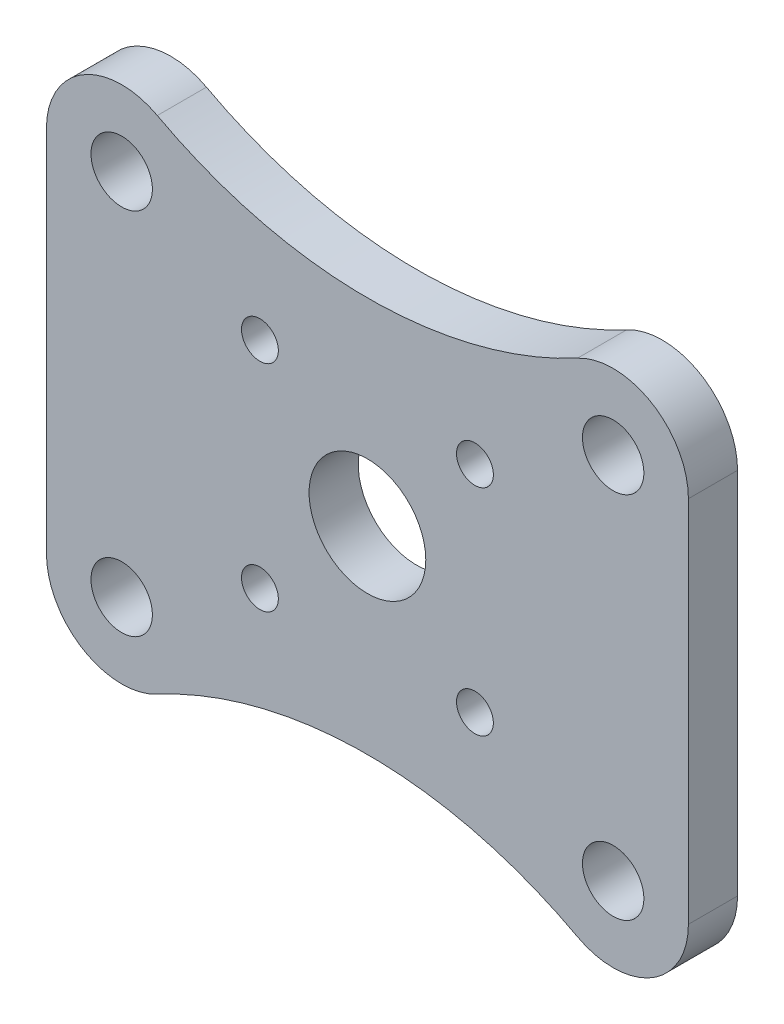
SolidWorks part; units mm, degrees
ref_plane "Front Plane" through (0, 0, 0) normal (0, 0, 1) x (1, 0, 0)
ref_plane "Top Plane" through (0, 0, 0) normal (0, 1, 0) x (1, 0, 0)
ref_plane "Right Plane" through (0, 0, 0) normal (1, 0, 0) x (0, 0, -1)
sketch "Sketch6" plane through (0, 0, 0) normal (0, 0, 1) x (1, 0, 0)
  line L0 (0, 16.0916) -> (0, 0) construction
  line L2 (0, 0) -> (0, -16.0916) construction
  line L3 (-26.1236, 15) -> (-26.1236, -15)
  line L4 (26.1236, 15) -> (26.1236, -15)
  circle A0 centre (-20, 15) radius 6.1236
  arc A1 (-17.102, 20.3945) -> (17.102, 20.3945) centre (0, 52.2292) ccw
  circle A2 centre (-20, -15) radius 6.1236
  arc A3 (-17.102, -20.3945) -> (17.102, -20.3945) centre (0, -52.2292) cw
  circle A6 centre (20, 15) radius 6.1236
  circle A7 centre (20, -15) radius 6.1236
extrude "Boss-Extrude1" add sketch "Sketch6" along normal blind 4 contours A7 L4 A6 A1 A0 L3 A2 A3 | A2 | A0 | A6 | A7
sketch "Sketch1" plane through (0, 0, 0) normal (0, 0, 1) x (1, 0, 0)
  line L0 (-8.75, 8.75) -> (8.75, 8.75) construction
  line L1 (8.75, 8.75) -> (8.75, -8.75) construction
  line L2 (8.75, -8.75) -> (-8.75, -8.75) construction
  line L3 (-8.75, -8.75) -> (-8.75, 8.75) construction
  line L4 (-8.75, 8.75) -> (8.75, -8.75) construction
  line L5 (8.75, 8.75) -> (-8.75, -8.75) construction
  circle A0 centre (-8.75, -8.75) radius 1.5
  circle A1 centre (-8.75, 8.75) radius 1.5
  circle A2 centre (8.75, 8.75) radius 1.5
  circle A3 centre (8.75, -8.75) radius 1.5
  circle A4 centre (0, 0) radius 4.75
  dimension "D7" = 3
  dimension "D13" = 9.5
  dimension "D4" = 17.5
sketch "Sketch4" plane through (0, 0, 0) normal (0, 0, 1) x (1, 0, 0)
  line L2 (-20, 15) -> (0, 0) construction
  circle A0 centre (-20, 15) radius 2.5
  circle A1 centre (20, 15) radius 2.5
  circle A2 centre (20, -15) radius 2.5
  circle A3 centre (-20, -15) radius 2.5
  dimension "D5" = 5
  dimension "D1" = 20
  dimension "D2" = 15
  dimension "D3" = 2
  dimension "D4" = 2
extrude "Cut-Extrude1" cut sketch "Sketch1" along normal through all
extrude "Cut-Extrude2" cut sketch "Sketch4" along normal through all
